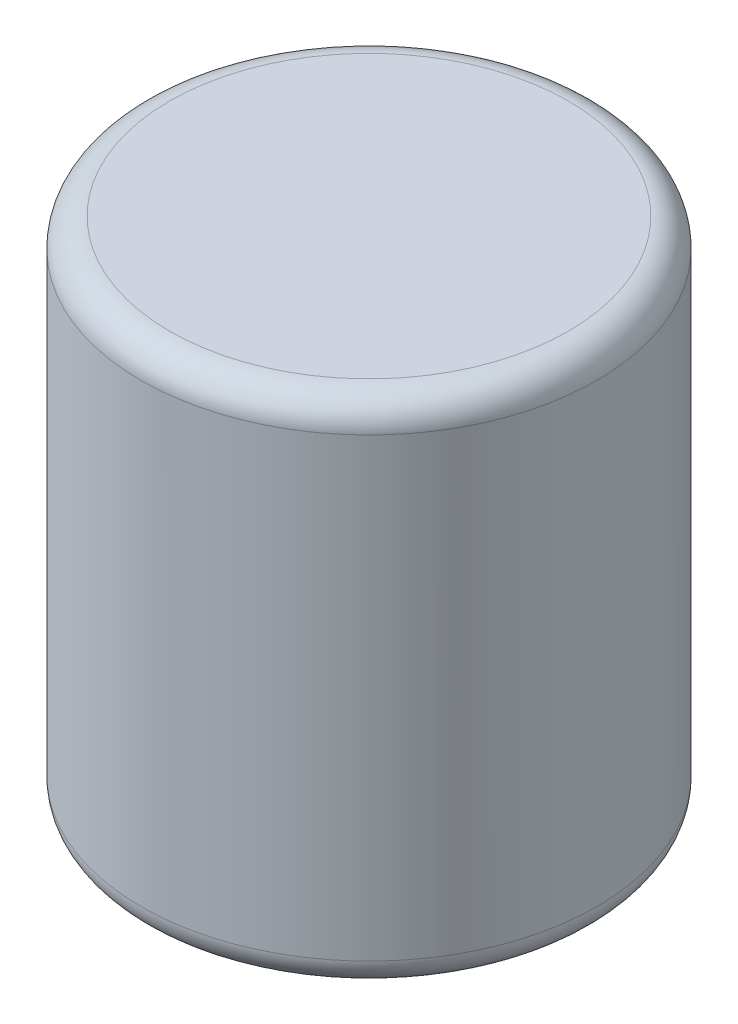
SolidWorks part; units mm, degrees
ref_plane "Front Plane" through (0, 0, 0) normal (0, 0, 1) x (1, 0, 0)
ref_plane "Top Plane" through (0, 0, 0) normal (0, 1, 0) x (1, 0, 0)
ref_plane "Right Plane" through (0, 0, 0) normal (1, 0, 0) x (0, 0, -1)
sketch "Sketch1" plane through (0, 0, 0) normal (0, 0, 1) x (1, 0, 0)
  line L0 (0, 0) -> (0, 18) construction
  line L1 (0, 18) -> (8, 18)
  line L2 (8, 18) -> (8, 0)
  line L3 (8, 0) -> (6.2, 0)
  line L4 (6.2, 0) -> (6.2, 0.75)
  line L5 (6.2, 0.75) -> (6.5, 0.75)
  line L6 (6.5, 0.75) -> (6.5, 14.5)
  line L7 (6.5, 14.5) -> (6.2, 14.5)
  line L8 (6.2, 14.5) -> (6.2, 15.25)
  line L9 (6.2, 15.25) -> (5.5, 15.25)
  line L10 (5.5, 15.25) -> (5.5, 16.5)
  line L11 (5.5, 16.5) -> (0, 16.5)
  line L12 (0, 16.5) -> (0, 18)
  point P12 (4.6843, 15.9257)
  point P15 (6.0479, 14.4769)
  point P16 (7.3263, 12.886)
  point P17 (7.582, 2.0909)
  point P18 (8, 0)
  point P19 (8, 0)
  point P20 (3.9023, 15.8607)
  point P21 (0, 0)
  point P22 (5.5173, 14.4406)
  point P23 (6.4918, 12.937)
  point P24 (7.4388, 0)
  point P25 (7.124, 0)
  point P26 (5.5283, 2.7917)
  point P27 (0, 0)
  point P28 (5.4733, 0)
  point P29 (5.5833, 1.9113)
  dimension "D1" = 18
  dimension "D2" = 8
  dimension "D3" = 1.5
  dimension "D4" = 1.8
  dimension "D5" = 0.75
  dimension "D6" = 0.3
  dimension "D7" = 1.5
  dimension "D8" = 3.5
  dimension "D9" = 2.5
  dimension "D10" = 0.3
  dimension "D11" = 1.5
  dimension "D12" = 0.75
  dimension "D13" = 0.7
  dimension "D14" = 1.25
revolve "Revolve1" add sketch "Sketch1" angle 360 about L0
fillet "Fillet1" radius 1 2 edges at (0, 0, -8) (0, 18, -8)
